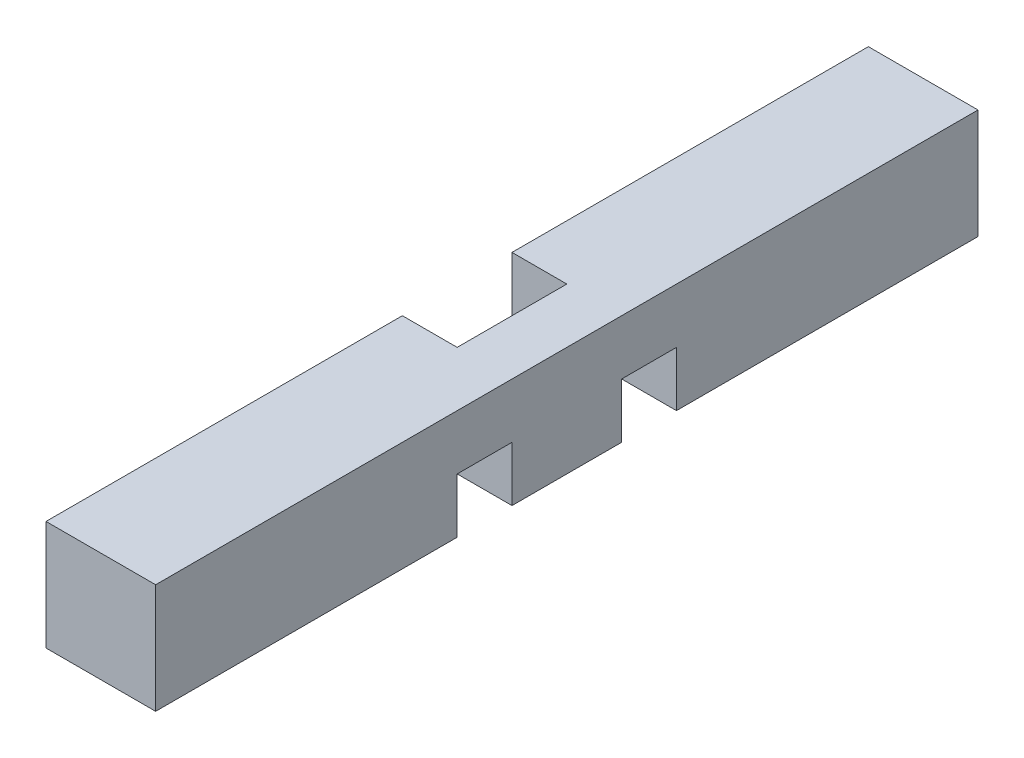
SolidWorks part; units mm, degrees
ref_plane "前基準面" through (0, 0, 0) normal (0, 0, 1) x (1, 0, 0)
ref_plane "上基準面" through (0, 0, 0) normal (0, 1, 0) x (1, 0, 0)
ref_plane "右基準面" through (0, 0, 0) normal (1, 0, 0) x (0, 0, -1)
sketch "草圖1" plane through (0, 0, 0) normal (0, 0, 1) x (1, 0, 0)
  line L1 (-2, 2) -> (2, 2)
  line L2 (-2, 2) -> (-2, -2)
  line L3 (-2, -2) -> (2, -2)
  line L4 (2, 2) -> (2, -2)
  line L5 (-2, 2) -> (2, -2) construction
  line L6 (-2, -2) -> (2, 2) construction
  point P0 (0, 0)
extrude "填料-伸長1" add sketch "草圖1" along normal blind 30 contours L2 L3 L4 L1
sketch "草圖2" plane through (-2, 0, 0) normal (-1, 0, 0) x (0, 0, 1)
  line L0 (30, 2) -> (0, 2) construction
  line L1 (30, -2) -> (19, -2)
  line L2 (30, -2) -> (30, 2)
  line L3 (30, 2) -> (19, 2)
  line L4 (19, -2) -> (19, 2)
sketch "草圖3" plane through (-2, 0, 0) normal (-1, 0, 0) x (0, 0, 1)
  line L1 (19, -2) -> (11, -2)
  line L2 (19, -2) -> (19, 0)
  line L3 (19, 0) -> (11, 0)
  line L4 (11, -2) -> (11, 0)
extrude "除料-伸長1" cut sketch "草圖3" against normal blind 2 contours L3 L4 L1 L2
sketch "草圖5" plane through (0, 0, 0) normal (-1, 0, 0) x (0, 0, 1)
  line L0 (19, 0) -> (11, 0) construction
  line L1 (19, -2) -> (17, -2)
  line L2 (19, -2) -> (19, 0)
  line L3 (19, 0) -> (17, 0)
  line L4 (17, -2) -> (17, 0)
extrude "除料-伸長2" cut sketch "草圖5" against normal blind 2
sketch "草圖6" plane through (0, 0, 0) normal (-1, 0, 0) x (0, 0, 1)
  line L0 (17, 0) -> (11, 0) construction
  line L1 (11, -2) -> (13, -2)
  line L2 (11, -2) -> (11, 0)
  line L3 (11, 0) -> (13, 0)
  line L4 (13, -2) -> (13, 0)
extrude "除料-伸長3" cut sketch "草圖6" against normal blind 2
sketch "草圖8" plane through (0, 0, 0) normal (0, -1, 0) x (1, 0, 0)
  line L0 (-2, 19) -> (-2, 11) construction
  line L1 (0, 17) -> (-2, 17)
  line L2 (0, 17) -> (0, 13)
  line L3 (0, 13) -> (-2, 13)
  line L4 (-2, 17) -> (-2, 13)
extrude "除料-伸長4" cut sketch "草圖8" against normal blind 2 contours L3 L4 L1 L2
